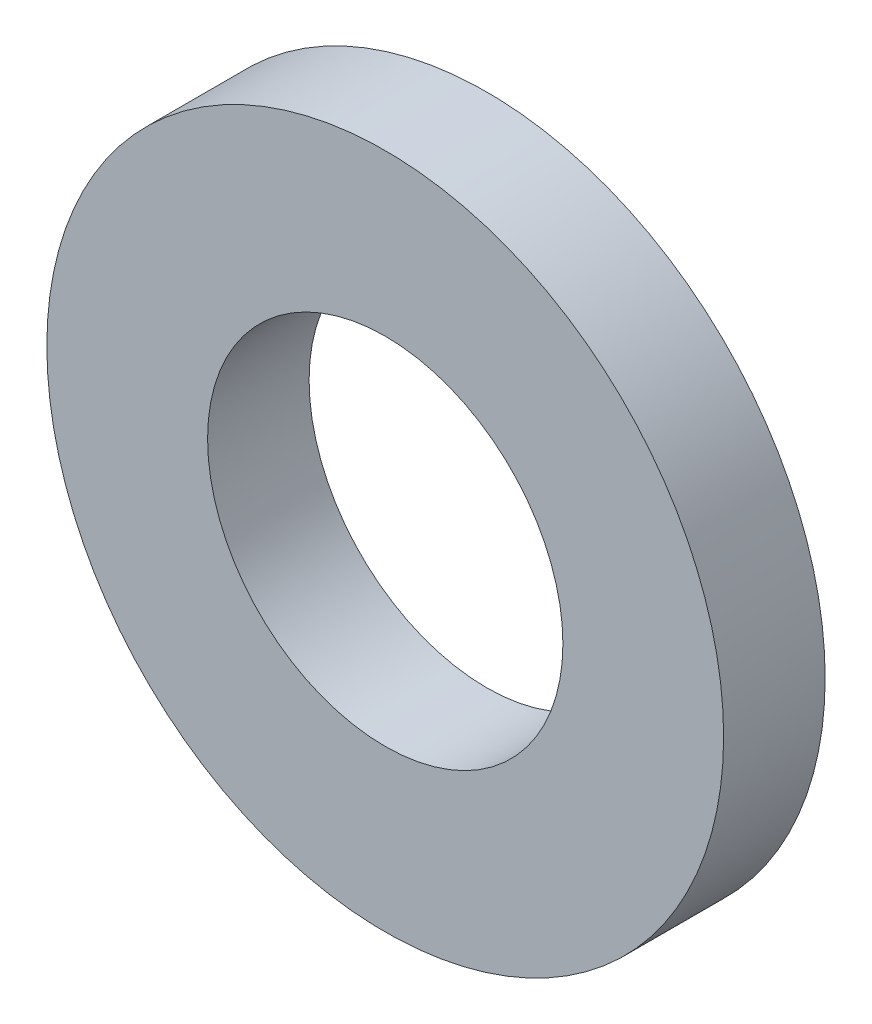
SolidWorks part; units mm, degrees
ref_plane "Front Plane" through (0, 0, 0) normal (0, 0, 1) x (1, 0, 0)
ref_plane "Top Plane" through (0, 0, 0) normal (0, 1, 0) x (1, 0, 0)
ref_plane "Right Plane" through (0, 0, 0) normal (1, 0, 0) x (0, 0, -1)
sketch "Sketch1" plane through (0, 0, 0) normal (0, 0, 1) x (1, 0, 0)
  circle A0 centre (0, 0) radius 2
  circle A1 centre (0, 0) radius 1.05
  dimension "OD" = 4
  dimension "ID1" = 2.1
extrude "Boss-Extrude1" add sketch "Sketch1" along normal blind 0.6
